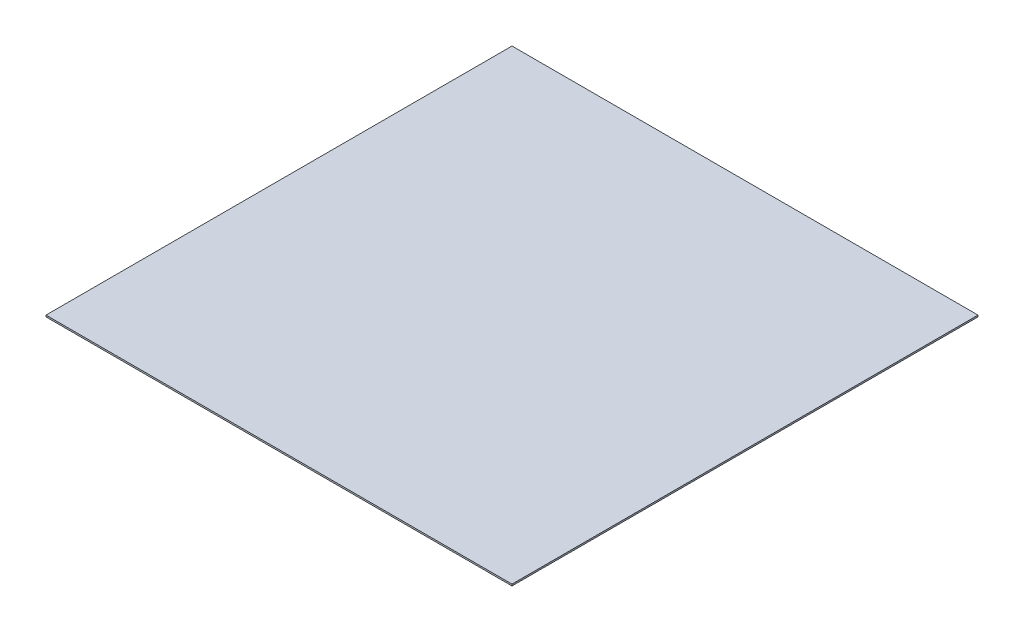
SolidWorks part; units mm, degrees
ref_plane "Front Plane" through (0, 0, 0) normal (0, 0, 1) x (1, 0, 0)
ref_plane "Top Plane" through (0, 0, 0) normal (0, 1, 0) x (1, 0, 0)
ref_plane "Right Plane" through (0, 0, 0) normal (1, 0, 0) x (0, 0, -1)
sketch "Sketch1" plane through (0, 0, 0) normal (0, 1, 0) x (1, 0, 0)
  line L1 (-457.2, -457.2) -> (457.2, -457.2)
  line L2 (-457.2, -457.2) -> (-457.2, 457.2)
  line L3 (-457.2, 457.2) -> (457.2, 457.2)
  line L4 (457.2, -457.2) -> (457.2, 457.2)
  line L5 (-457.2, -457.2) -> (457.2, 457.2) construction
  line L6 (-457.2, 457.2) -> (457.2, -457.2) construction
  point P0 (0, 0)
  dimension "D1" = 914.4
extrude "Square Board" add sketch "Sketch1" along normal blind 3.175
sketch "Game Board Bounds" plane through (0, 3.175, 0) normal (0, 1, 0) x (1, 0, 0)
  circle A0 centre (0, 0) radius 304.8 construction
  dimension "D1" = 609.6
sketch "Init Marble Positions" plane through (0, 3.175, 0) normal (0, 1, 0) x (1, 0, 0)
  line L1 (-39.444, 147.2071) -> (0, 0) construction
  line L2 (0, 0) -> (0, 152.4) construction
  circle A0 centre (0, 0) radius 152.4 construction
  circle A2 centre (-39.444, 147.2071) radius 10
  circle A3 centre (39.444, 147.2071) radius 10
  circle A4 centre (107.7631, 107.7631) radius 10
  circle A5 centre (147.2071, 39.444) radius 10
  circle A6 centre (147.2071, -39.444) radius 10
  circle A7 centre (107.7631, -107.7631) radius 10
  circle A8 centre (39.444, -147.2071) radius 10
  circle A9 centre (-39.444, -147.2071) radius 10
  circle A10 centre (-107.7631, -107.7631) radius 10
  circle A11 centre (-147.2071, -39.444) radius 10
  circle A12 centre (-147.2071, 39.444) radius 10
  circle A13 centre (-107.7631, 107.7631) radius 10
  point P30 (0, 0)
  dimension "D1" = 304.8
  dimension "D2" = 20
  dimension "D3" = 15
  dimension "D4" = 12
